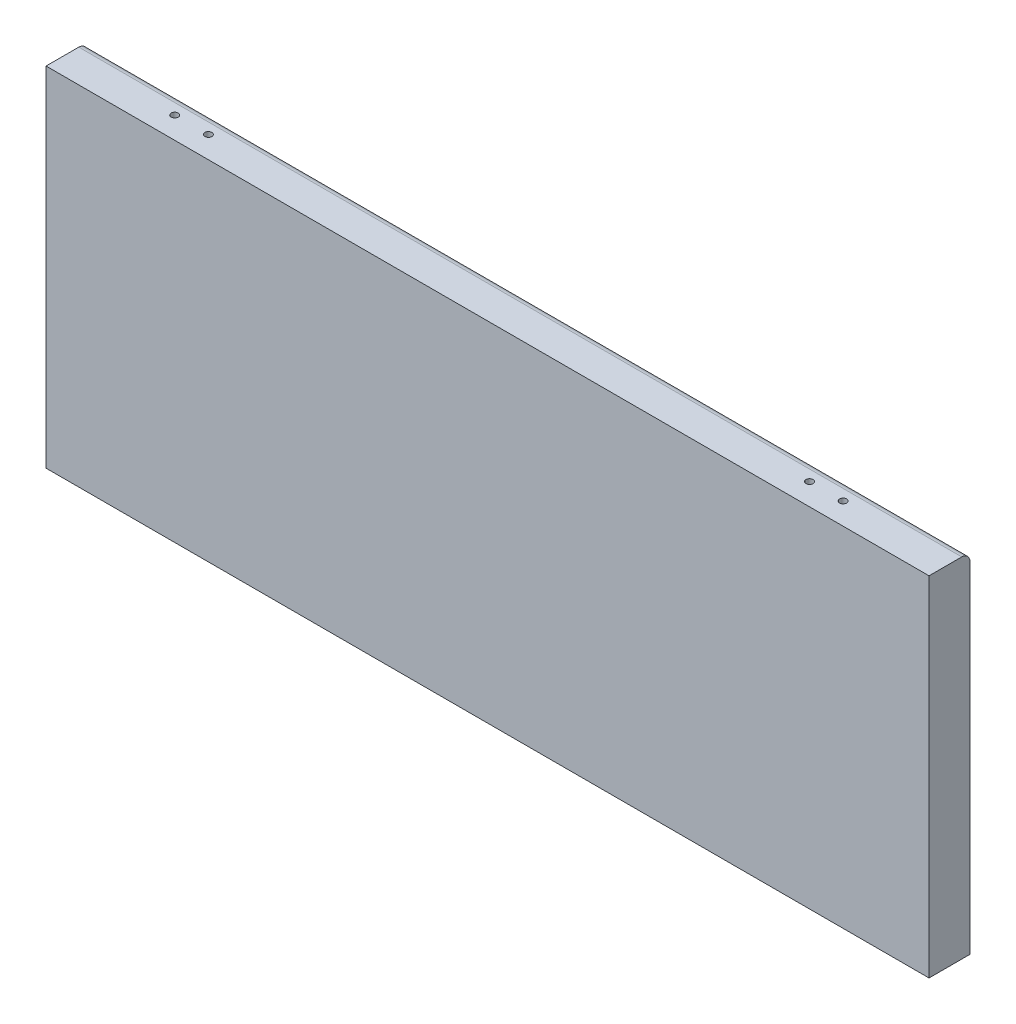
SolidWorks part; units mm, degrees
ref_plane "Front Plane" through (0, 0, 0) normal (0, 0, 1) x (1, 0, 0)
ref_plane "Top Plane" through (0, 0, 0) normal (0, 1, 0) x (1, 0, 0)
ref_plane "Right Plane" through (0, 0, 0) normal (1, 0, 0) x (0, 0, -1)
sketch "Sketch1" plane through (0, 0, 0) normal (0, 0, 1) x (1, 0, 0)
  line L1 (358.3213, 127.7126) -> (34.572, 127.7126)
  line L2 (358.3213, 127.7126) -> (358.3213, 0)
  line L3 (358.3213, 0) -> (34.572, 0)
  line L4 (34.572, 127.7126) -> (34.572, 0)
extrude "Boss-Extrude1" add sketch "Sketch1" along normal blind 4 from offset 80 offset against normal yes
sketch "Sketch4" plane through (0, 0, -76) normal (0, 0, 1) x (1, 0, 0)
  line L1 (34.572, 127.7126) -> (358.3213, 127.7126)
  line L2 (34.572, 127.7126) -> (34.572, 0)
  line L3 (34.572, 0) -> (358.3213, 0)
  line L4 (358.3213, 127.7126) -> (358.3213, 0)
  line L5 (38.572, 123.7126) -> (354.3213, 123.7126)
  line L6 (38.572, 123.7126) -> (38.572, 4)
  line L7 (38.572, 4) -> (354.3213, 4)
  line L8 (354.3213, 123.7126) -> (354.3213, 4)
  dimension "D1" = 4
  dimension "D2" = 4
  dimension "D3" = 4
  dimension "D4" = 4
extrude "Boss-Extrude2" add sketch "Sketch4" against normal blind 15
sketch "Sketch6" plane through (0, 0, 0) normal (0, -1, 0) x (1, 0, 0)
  circle A0 centre (207.9467, -84.5) radius 1.55
  circle A1 centre (184.9467, -84.5) radius 1.55
extrude "Cut-Extrude2" cut sketch "Sketch6" against normal blind 6
sketch "Sketch10" plane through (0, 127.7126, 0) normal (0, 1, 0) x (1, 0, 0)
  line L0 (34.572, 76) -> (34.572, 91) construction
  line L1 (358.3213, 76) -> (358.3213, 91) construction
  circle A0 centre (306.4897, 84.0152) radius 1.2999
  circle A1 centre (318.8218, 84.0152) radius 1.2999
  circle A2 centre (73.7382, 84.0152) radius 1.2999
  circle A3 centre (86.0703, 84.0152) radius 1.2999
  dimension "D1" = 39.1663
  dimension "D2" = 12.3321
  dimension "D3" = 39.4995
extrude "Cut-Extrude3" cut sketch "Sketch10" against normal blind 6
fillet "Fillet1" radius 3 1 edges at (196.4467, 127.7126, -91)
